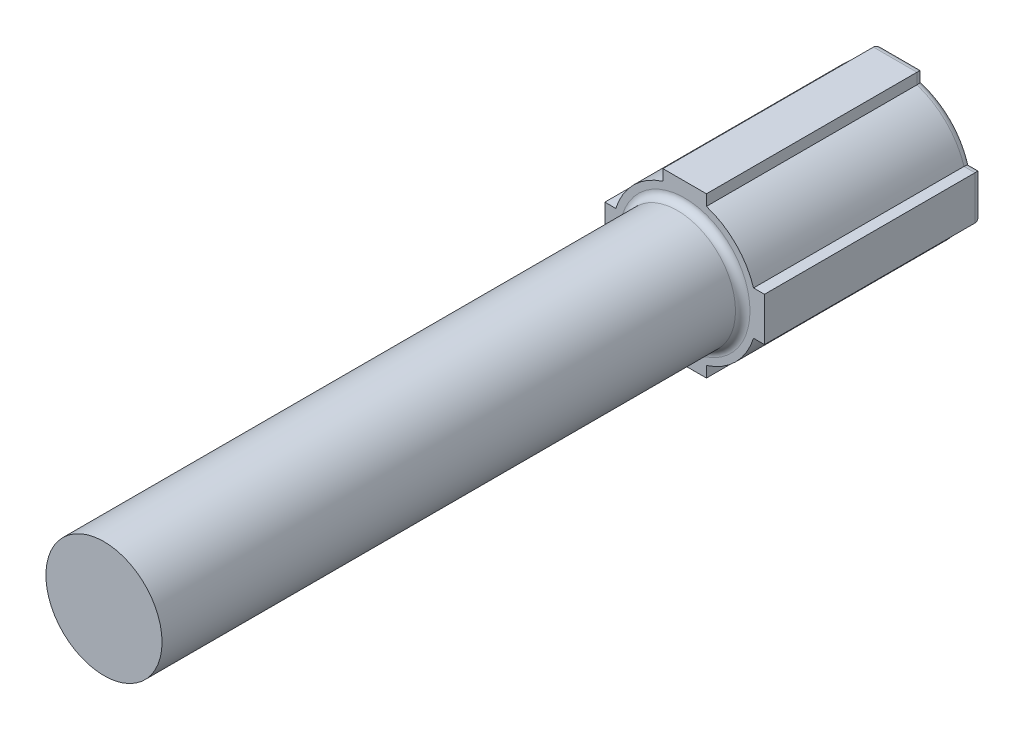
SolidWorks part; units mm, degrees
material "Alloy Steel"
ref_plane "Front Plane" through (0, 0, 0) normal (0, 0, 1) x (1, 0, 0)
ref_plane "Top Plane" through (0, 0, 0) normal (0, 1, 0) x (1, 0, 0)
ref_plane "Right Plane" through (0, 0, 0) normal (1, 0, 0) x (0, 0, -1)
sketch "Sketch1" plane through (0, 0, 0) normal (0, 0, 1) x (1, 0, 0)
  line L1 (-3, -10.995) -> (3, -10.995)
  line L2 (-3, -10.995) -> (-3, 10.995)
  line L3 (-3, 10.995) -> (3, 10.995)
  line L4 (3, -10.995) -> (3, 10.995)
  line L5 (-3, -10.995) -> (3, 10.995) construction
  line L6 (-3, 10.995) -> (3, -10.995) construction
  line L7 (-10.995, -3) -> (10.995, -3)
  line L8 (-10.995, -3) -> (-10.995, 3)
  line L9 (-10.995, 3) -> (10.995, 3)
  line L10 (10.995, -3) -> (10.995, 3)
  line L11 (-10.995, -3) -> (10.995, 3) construction
  line L12 (-10.995, 3) -> (10.995, -3) construction
  circle A0 centre (0, 0) radius 9.95
  dimension "D1" = 19.9
  dimension "D2" = 21.99
  dimension "D3" = 6
  dimension "D4" = 6
  dimension "D5" = 21.99
extrude "Boss-Extrude1" add sketch "Sketch1" along normal mid plane 30 contours A0 L9 L8 L7 | A0 L7 L10 L9 | A0 L4 L3 L2 | A0 L2 L1 L4
sketch "Sketch2" plane through (0, 0, 15) normal (0, 0, 1) x (1, 0, 0)
  circle A0 centre (0, 0) radius 8
extrude "Boss-Extrude2" add sketch "Sketch2" along normal blind 80
fillet "Fillet1" radius 1 17 edges at (-10.995, 0, -15) (-10.241, -3, -15) (-7.0357, -7.0357, -15) (-3, -10.241, -15) (0, -10.995, -15) (3, -10.241, -15) (7.0357, -7.0357, -15) (10.241, -3, -15) (10.995, 0, -15) (10.241, 3, -15) (7.0357, 7.0357, -15) (3, 10.241, -15) (0, 10.995, -15) (-3, 10.241, -15) (-7.0357, 7.0357, -15) (-10.241, 3, -15) (8, 0, 15)
